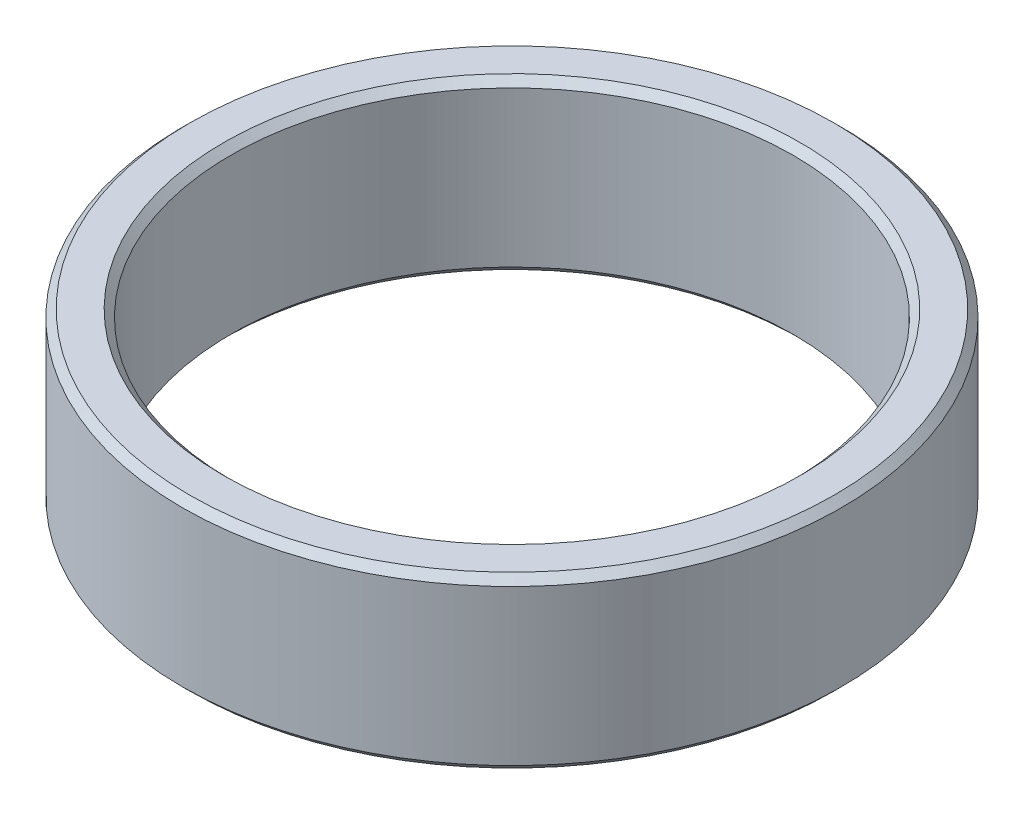
SolidWorks part; units mm, degrees
ref_plane "前视基准面" through (0, 0, 0) normal (0, 0, 1) x (1, 0, 0)
ref_plane "上视基准面" through (0, 0, 0) normal (0, 1, 0) x (1, 0, 0)
ref_plane "右视基准面" through (0, 0, 0) normal (1, 0, 0) x (0, 0, -1)
sketch "草图1" plane through (0, 0, 0) normal (0, 1, 0) x (1, 0, 0)
  circle A0 centre (0, 0) radius 13.6
  circle A1 centre (0, 0) radius 11.6
  dimension "D1" = 27.2
  dimension "D2" = 2
extrude "凸台-拉伸1" add sketch "草图1" along normal blind 7
chamfer "倒角1" distance 0.3 angle 45 4 edges at (0, 7, 11.6) (0, 7, 13.6) (0, 0, 11.6) (0, 0, 13.6)
